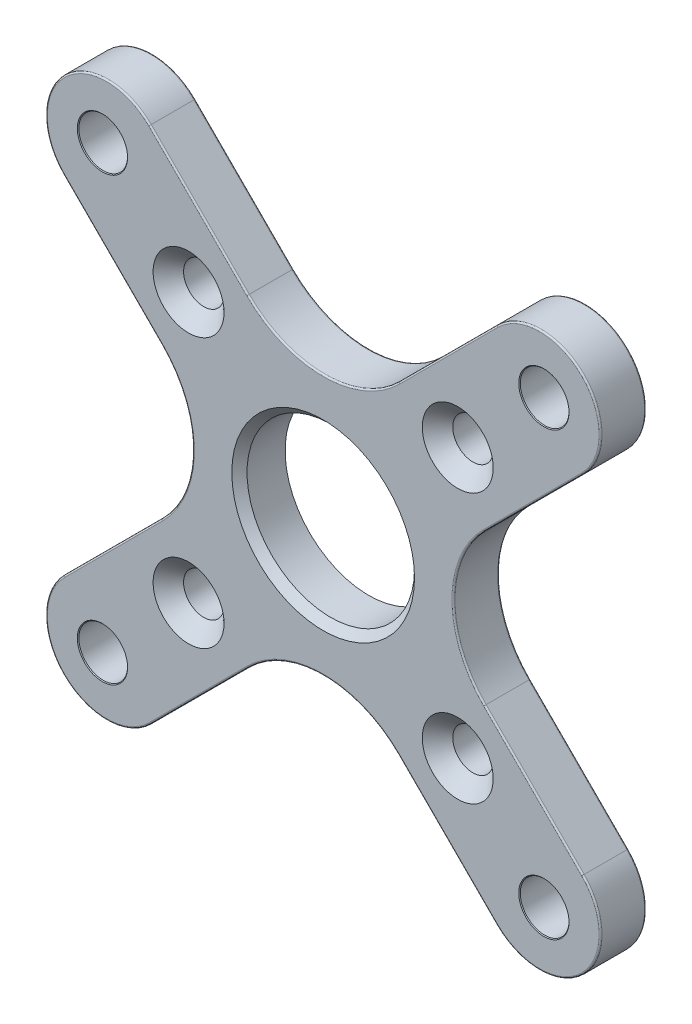
SolidWorks part; units mm, degrees
material "Thornel Mat VMA"
ref_plane "Front Plane" through (0, 0, 0) normal (0, 0, 1) x (1, 0, 0)
ref_plane "Top Plane" through (0, 0, 0) normal (0, 1, 0) x (1, 0, 0)
ref_plane "Right Plane" through (0, 0, 0) normal (1, 0, 0) x (0, 0, -1)
sketch "Sketch1" plane through (0, 0, 0) normal (0, 0, 1) x (1, 0, 0)
  line L0 (-4.9497, -10.6066) -> (-7.0268, -12.6836) construction
  line L1 (7.0268, -12.6836) -> (4.9497, -10.6066) construction
  line L2 (12.6836, 7.0268) -> (10.6066, 4.9497) construction
  line L3 (10.6066, -4.9497) -> (12.6836, -7.0268) construction
  line L4 (-7.0268, 12.6836) -> (-4.9497, 10.6066) construction
  line L5 (4.9497, 10.6066) -> (7.0268, 12.6836) construction
  line L6 (-12.6836, -7.0268) -> (-10.6066, -4.9497) construction
  line L7 (-10.6066, 4.9497) -> (-12.6836, 7.0268) construction
  line L8 (-4.9497, -10.6066) -> (-7.0268, -12.6836)
  line L9 (7.0268, -12.6836) -> (4.9497, -10.6066)
  line L10 (12.6836, 7.0268) -> (10.6066, 4.9497)
  line L11 (10.6066, -4.9497) -> (12.6836, -7.0268)
  line L12 (-7.0268, 12.6836) -> (-4.9497, 10.6066)
  line L13 (4.9497, 10.6066) -> (7.0268, 12.6836)
  line L14 (-12.6836, -7.0268) -> (-10.6066, -4.9497)
  line L15 (-10.6066, 4.9497) -> (-12.6836, 7.0268)
  line L16 (-12.6836, 7.0268) -> (-17.0455, 11.3886)
  line L17 (-17.0455, 11.3886) -> (-11.3886, 17.0455) construction
  line L18 (-11.3886, 17.0455) -> (-7.0268, 12.6836)
  line L19 (7.0268, 12.6836) -> (11.3886, 17.0455)
  line L20 (17.0455, 11.3886) -> (12.6836, 7.0268)
  line L21 (11.3886, 17.0455) -> (17.0455, 11.3886) construction
  line L22 (12.6836, -7.0268) -> (17.0455, -11.3886)
  line L23 (11.3886, -17.0455) -> (7.0268, -12.6836)
  line L24 (17.0455, -11.3886) -> (11.3886, -17.0455) construction
  line L25 (-7.0268, -12.6836) -> (-11.3886, -17.0455)
  line L26 (-17.0455, -11.3886) -> (-12.6836, -7.0268)
  line L27 (-11.3886, -17.0455) -> (-17.0455, -11.3886) construction
  circle A0 centre (0, 0) radius 7.25 construction
  circle A1 centre (0, 0) radius 7.25
  circle A2 centre (-8.8388, 8.8388) radius 1.3295 construction
  circle A3 centre (-8.8388, 8.8388) radius 1.3295
  circle A4 centre (8.8388, 8.8388) radius 1.3295 construction
  circle A5 centre (8.8388, -8.8388) radius 1.3295 construction
  circle A6 centre (-8.8388, -8.8388) radius 1.3295 construction
  circle A7 centre (8.8388, 8.8388) radius 1.3295
  circle A8 centre (8.8388, -8.8388) radius 1.3295
  circle A9 centre (-8.8388, -8.8388) radius 1.3295
  arc A10 (4.9497, -10.6066) -> (-4.9497, -10.6066) centre (0, -15.5563) ccw construction
  arc A11 (10.6066, 4.9497) -> (10.6066, -4.9497) centre (15.5563, 0) ccw construction
  arc A12 (-4.9497, 10.6066) -> (4.9497, 10.6066) centre (0, 15.5563) ccw construction
  arc A13 (-10.6066, -4.9497) -> (-10.6066, 4.9497) centre (-15.5563, 0) ccw construction
  arc A14 (4.9497, -10.6066) -> (-4.9497, -10.6066) centre (0, -15.5563) ccw
  arc A15 (10.6066, 4.9497) -> (10.6066, -4.9497) centre (15.5563, 0) ccw
  arc A16 (-4.9497, 10.6066) -> (4.9497, 10.6066) centre (0, 15.5563) ccw
  arc A17 (-10.6066, -4.9497) -> (-10.6066, 4.9497) centre (-15.5563, 0) ccw
  circle A18 centre (0, 0) radius 15.2738 construction
  circle A19 centre (0, 0) radius 15.2738
  circle A20 centre (0, 0) radius 20.5 construction
  arc A21 (-11.3886, 17.0455) -> (-17.0455, 11.3886) centre (-14.2171, 14.2171) ccw
  arc A22 (17.0455, 11.3886) -> (11.3886, 17.0455) centre (14.2171, 14.2171) ccw
  arc A23 (11.3886, -17.0455) -> (17.0455, -11.3886) centre (14.2171, -14.2171) ccw
  arc A24 (-17.0455, -11.3886) -> (-11.3886, -17.0455) centre (-14.2171, -14.2171) ccw
  point P59 (0, 0)
  dimension "D1" = 41
  dimension "D2" = 4
extrude "Boss-Extrude1" add sketch "Sketch1" along normal blind 3 contours L26 A24 L25 A19 | L20 A19 L19 L13 A16 L12 L18 L16 L15 A17 L14 L26 L25 L8 A14 L9 L23 L22 L11 A15 L10 A1 A3 A7 A8 A9 | L23 A23 L22 A19 | L20 A22 L19 A19 | L18 A21 L16 A19
hole_wizard "Ø3.2 (3.2) Diameter Hole1" positions "Sketch3" profile "Sketch4" hole size "Ø3.2" standard "ISO" end condition through all
sketch "Sketch3" plane through (0, 0, 0) normal (0, 0, -1) x (-1, 0, 0)
  line L2 (-14.4957, 14.4957) -> (14.4957, -14.4957) construction
  line L4 (0, 0) -> (0, -20.5) construction
  line L5 (14.4957, 14.4957) -> (-14.4957, -14.4957) construction
  circle A0 centre (0, 0) radius 20.5
  point P25 (-14.4957, 14.4957)
  point P27 (14.4957, -14.4957)
  point P40 (14.4957, 14.4957)
  point P41 (-14.4957, -14.4957)
  dimension "D1" = 41
  dimension "D2" = 45
sketch "Sketch4" plane through (14.4957, 14.4957, 0) normal (1, 0, 0) x (0, 1, 0)
  line L0 (0, 0) -> (0, 3)
  line L1 (0, 3) -> (1.6, 3)
  line L2 (1.6, 3) -> (1.6, 0)
  line L5 (1.6, 0) -> (0, 0)
  line L11 (0, -6.35) -> (0, 107.95) construction
  dimension "Thru Hole Dia." = 3.2
  dimension "Thru Hole Depth" = 3
chamfer "Chamfer1" distance 1 angle 45 4 edges at (10.1683, 8.8388, 3) (-7.5093, 8.8388, 3) (-7.5093, -8.8388, 3) (10.1683, -8.8388, 3)
sketch "Sketch7" plane through (0, 0, 3) normal (0, 0, 1) x (1, 0, 0)
  circle A0 centre (0, 0) radius 7.25
  circle A1 centre (0, 0) radius 5.5
  circle A2 centre (0, 0) radius 7.25 construction
  dimension "D1" = 11
extrude "Boss-Extrude2" add sketch "Sketch7" against normal up to surface (3 mm away) up to face at (12.8957, 14.4957, 0)
chamfer "Chamfer2" distance 0.5 angle 45 1 edges at (5.5, 0, 3)
fillet "Fillet1" radius 0.1 32 edges at (13.826, 8.1692, 3) (17.0455, 17.0455, 3) (8.1692, 13.826, 3) (0, 8.5563, 3) (-8.1692, 13.826, 3) (-17.0455, 17.0455, 3) (-13.826, 8.1692, 3) (-8.5563, 0, 3) (-13.826, -8.1692, 3) (-17.0455, -17.0455, 3) (-8.1692, -13.826, 3) (0, -8.5563, 3) (8.1692, -13.826, 3) (17.0455, -17.0455, 3) (13.826, -8.1692, 3) (13.826, 8.1692, 0) (17.0455, 17.0455, 0) (8.1692, 13.826, 0) (0, 8.5563, 0) (-8.1692, 13.826, 0) (-17.0455, 17.0455, 0) (-13.826, 8.1692, 0) (-8.5563, 0, 0) (-13.826, -8.1692, 0) (-17.0455, -17.0455, 0) (-8.1692, -13.826, 0) (0, -8.5563, 0) (8.1692, -13.826, 0) (17.0455, -17.0455, 0) (13.826, -8.1692, 0) (8.5563, 0, 3) (8.5563, 0, 0)
chamfer "Chamfer3" distance 0.05 angle 45 4 edges at (-16.0957, 14.4957, 3) (-16.0957, -14.4957, 3) (12.8957, -14.4957, 3) (12.8957, 14.4957, 3)
